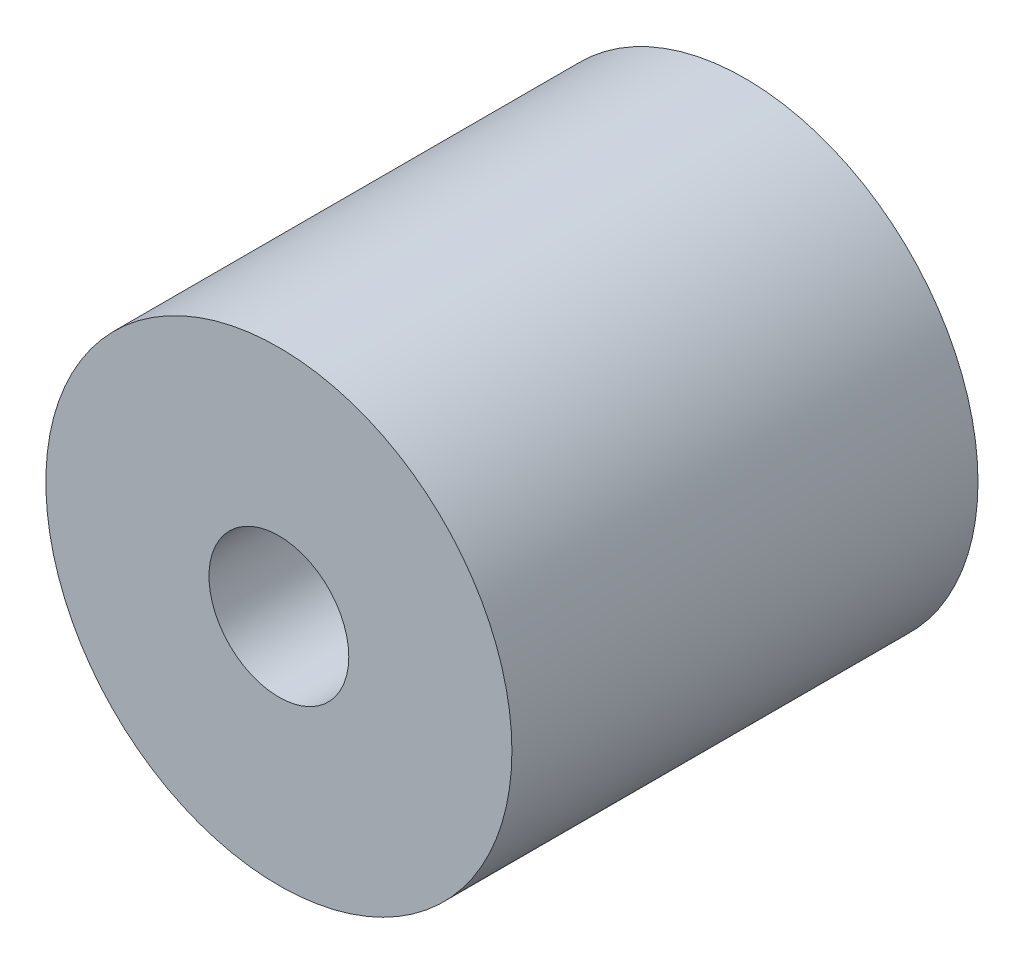
SolidWorks part; units mm, degrees
material "ABS PC"
ref_plane "Front Plane" through (0, 0, 0) normal (0, 0, 1) x (1, 0, 0)
ref_plane "Top Plane" through (0, 0, 0) normal (0, 1, 0) x (1, 0, 0)
ref_plane "Right Plane" through (0, 0, 0) normal (1, 0, 0) x (0, 0, -1)
sketch "Sketch1" plane through (0, 0, 0) normal (0, 0, 1) x (1, 0, 0)
  circle A0 centre (0, 0) radius 5
  circle A1 centre (0, 0) radius 1.5
  dimension "D1" = 10
  dimension "D2" = 3
extrude "Boss-Extrude1" add sketch "Sketch1" along normal blind 10
